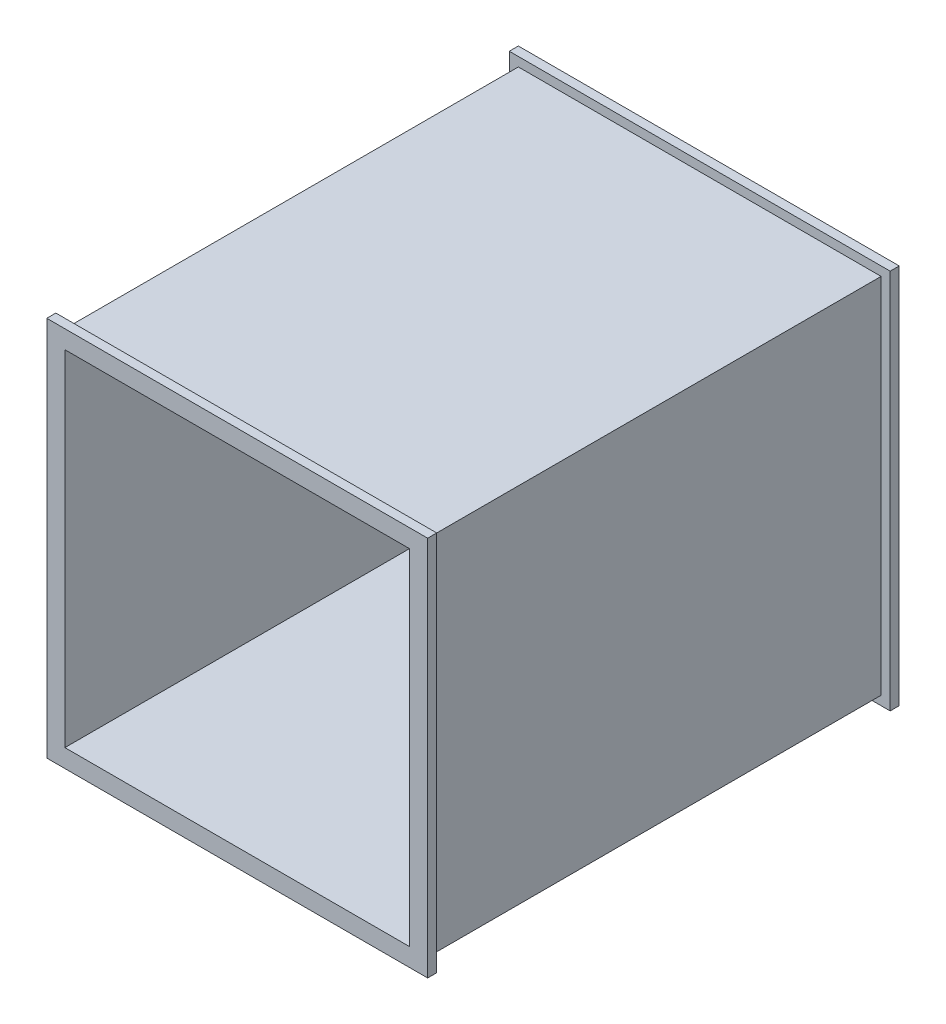
SolidWorks part; units mm, degrees
ref_plane "Front Plane" through (0, 0, 0) normal (0, 0, 1) x (1, 0, 0)
ref_plane "Top Plane" through (0, 0, 0) normal (0, 1, 0) x (1, 0, 0)
ref_plane "Right Plane" through (0, 0, 0) normal (1, 0, 0) x (0, 0, -1)
sketch "Sketch1" plane through (0, 0, 0) normal (0, 0, 1) x (1, 0, 0)
  line L1 (-100, 100) -> (100, 100)
  line L2 (-100, 100) -> (-100, -100)
  line L3 (-100, -100) -> (100, -100)
  line L4 (100, 100) -> (100, -100)
  line L5 (-100, 100) -> (100, -100) construction
  line L6 (-100, -100) -> (100, 100) construction
  point P0 (0, 0)
  dimension "D1" = 200
  dimension "D2" = 200
extrude "Boss-Extrude1" add sketch "Sketch1" along normal blind 250
sketch "Sketch2" plane through (0, 0, 250) normal (0, 0, 1) x (1, 0, 0)
  line L8 (105, -105) -> (105, 105)
  line L9 (105, 105) -> (-105, 105)
  line L10 (-105, 105) -> (-105, -105)
  line L11 (-105, -105) -> (105, -105)
  line L12 (105, -105) -> (105, 105)
  line L13 (105, 105) -> (-105, 105)
  line L14 (-105, 105) -> (-105, -105)
  line L15 (-105, -105) -> (105, -105)
  dimension "D1" = 5
extrude "Boss-Extrude2" add sketch "Sketch2" along normal blind 5
sketch "Sketch3" plane through (0, 0, 0) normal (0, 0, -1) x (-1, 0, 0)
  line L8 (-105, 105) -> (-105, -105)
  line L9 (-105, -105) -> (105, -105)
  line L10 (105, -105) -> (105, 105)
  line L11 (105, 105) -> (-105, 105)
  line L12 (-105, 105) -> (-105, -105)
  line L13 (-105, -105) -> (105, -105)
  line L14 (105, -105) -> (105, 105)
  line L15 (105, 105) -> (-105, 105)
  dimension "D1" = 5
extrude "Boss-Extrude3" add sketch "Sketch3" along normal blind 5
sketch "Sketch4" plane through (0, 0, 255) normal (0, 0, 1) x (1, 0, 0)
  line L1 (-95, 95) -> (95, 95)
  line L2 (-95, 95) -> (-95, -95)
  line L3 (-95, -95) -> (95, -95)
  line L4 (95, 95) -> (95, -95)
  line L5 (-95, 95) -> (95, -95) construction
  line L6 (-95, -95) -> (95, 95) construction
  point P0 (0, 0)
  dimension "D1" = 190
  dimension "D2" = 190
extrude "Cut-Extrude1" cut sketch "Sketch4" against normal through all contours L2 L1 L4 L3
